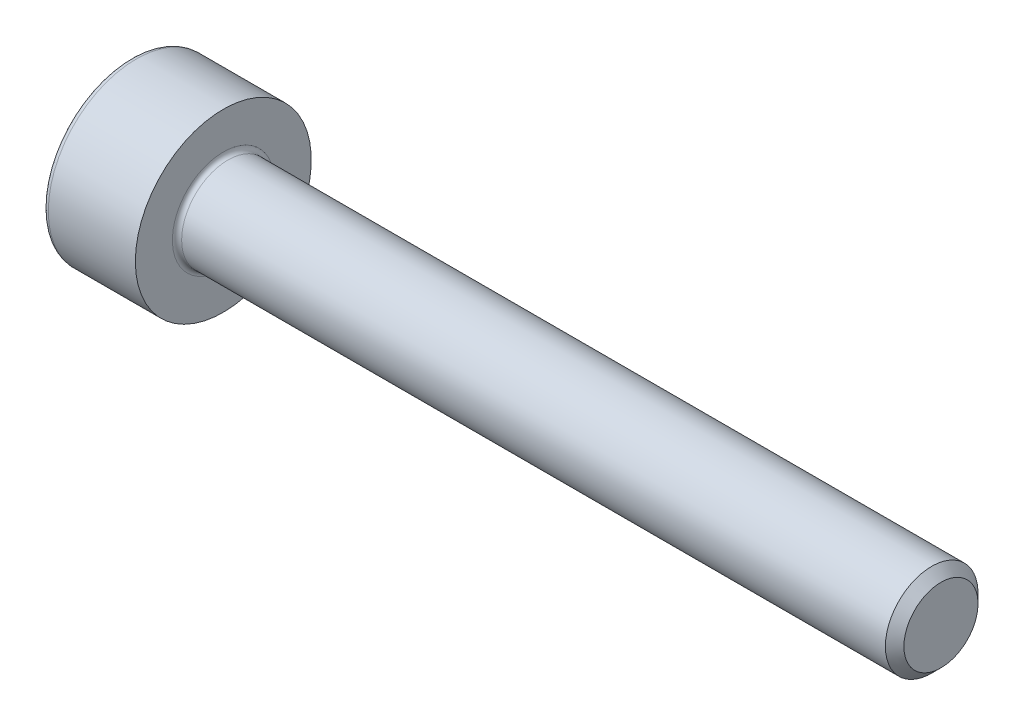
SolidWorks part; units mm, degrees
ref_plane "Front Plane" through (0, 0, 0) normal (0, 0, 1) x (1, 0, 0)
ref_plane "Top Plane" through (0, 0, 0) normal (0, 1, 0) x (1, 0, 0)
ref_plane "Right Plane" through (0, 0, 0) normal (1, 0, 0) x (0, 0, -1)
sketch "Sketch1" plane through (0, 0, 0) normal (0, 0, 1) x (1, 0, 0)
  line L0 (0, 0) -> (0, 1.9)
  line L1 (0, 1.9) -> (2, 1.9)
  line L2 (2, 1.9) -> (2, 0)
  line L3 (0, 0) -> (4.2799, 0) construction
  line L4 (2, 0) -> (17.5, 0)
  line L5 (17.5, 0) -> (17.5, 1)
  line L6 (17.5, 1) -> (2, 1)
  dimension "D1" = 15.5
revolve "Revolve1" add sketch "Sketch1" angle 360 about L3
fillet "Fillet1" radius 0.1 1 edges at (2, 0, 1)
fillet "Fillet2" radius 0.12 1 edges at (0, 0, 1.9)
chamfer "Chamfer1" distance 0.2 angle 45 1 edges at (17.5, 0, 1)
sketch "Sketch2" plane through (0, 0, 0) normal (-1, 0, 0) x (0, 0, 1)
  line L1 (0, 0.866) -> (-0.75, 0.433)
  line L2 (-0.75, 0.433) -> (-0.75, -0.433)
  line L3 (-0.75, -0.433) -> (0, -0.866)
  line L4 (0, -0.866) -> (0.75, -0.433)
  line L5 (0.75, -0.433) -> (0.75, 0.433)
  line L6 (0.75, 0.433) -> (0, 0.866)
  circle A0 centre (0, 0) radius 0.75 construction
extrude "Extrude1" cut sketch "Sketch2" against normal blind 1
